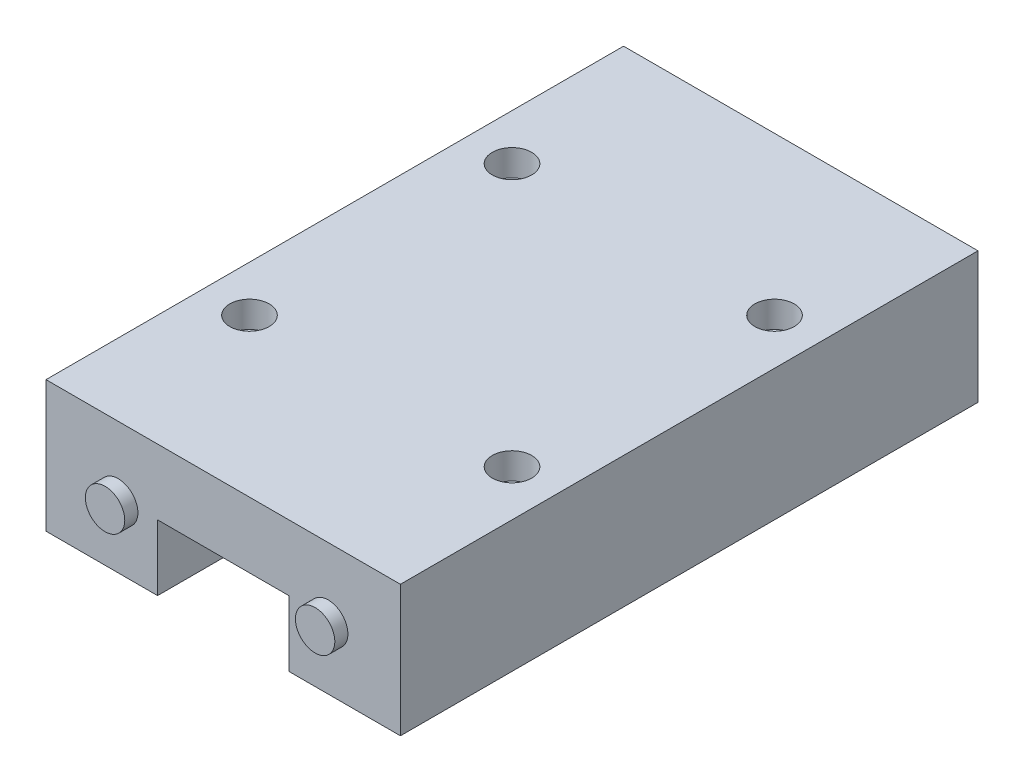
SolidWorks part; units mm, degrees
ref_plane "前基準面" through (0, 0, 0) normal (0, 0, 1) x (1, 0, 0)
ref_plane "上基準面" through (0, 0, 0) normal (0, 1, 0) x (1, 0, 0)
ref_plane "右基準面" through (0, 0, 0) normal (1, 0, 0) x (0, 0, -1)
sketch "草圖1" plane through (0, 0, 0) normal (0, 0, 1) x (1, 0, 0)
  line L0 (5, -5) -> (13.5, -5)
  line L1 (-13.5, 5) -> (13.5, 5)
  line L2 (-13.5, 5) -> (-13.5, -5)
  line L3 (-13.5, -5) -> (-5, -5)
  line L4 (13.5, 5) -> (13.5, -5)
  line L6 (-5, -5) -> (-5, 0)
  line L7 (-5, 0) -> (5, 0)
  line L8 (5, -5) -> (5, 0)
  point P4 (0, 5)
  point P6 (-13.5, 0)
  point P11 (0, 0)
  dimension "D1" = 27
  dimension "D2" = 10
  dimension "D3" = 10
  dimension "D4" = 5
extrude "填料-伸長1" add sketch "草圖1" along normal blind 44
sketch "草圖2" plane through (0, 5, 0) normal (0, 1, 0) x (1, 0, 0)
  line L0 (-13.5, -22) -> (13.5, -22) construction
  line L1 (-13.5, -44) -> (-13.5, 0) construction
  line L2 (13.5, -44) -> (13.5, 0) construction
  line L3 (0, -44) -> (0, 0) construction
  line L4 (13.5, -44) -> (-13.5, -44) construction
  circle A0 centre (-10, -32) radius 1.5
  circle A1 centre (10, -32) radius 1.5
  circle A2 centre (10, -12) radius 1.5
  circle A3 centre (-10, -12) radius 1.5
  dimension "D1" = 10
  dimension "D2" = 3
  dimension "D3" = 10
extrude "除料-伸長1" cut sketch "草圖2" against normal blind 2
sketch "草圖3" plane through (0, 0, 44) normal (0, 0, 1) x (1, 0, 0)
  line L0 (0, 5) -> (0, 0) construction
  line L1 (13.5, 5) -> (-13.5, 5) construction
  circle A0 centre (-8, -0.2841) radius 1.5
  circle A1 centre (8, -0.2841) radius 1.5
  dimension "D2" = 3
  dimension "D1" = 8
extrude "填料-伸長2" add sketch "草圖3" along normal blind 1
sketch "草圖4" plane through (0, 0, 0) normal (0, 0, -1) x (-1, 0, 0)
  line L0 (0, 0) -> (0, 5) construction
  line L1 (-13.5, 5) -> (13.5, 5) construction
  circle A0 centre (-8, 0) radius 1.5
  circle A1 centre (8, 0) radius 1.5
  dimension "D2" = 3
  dimension "D1" = 8
extrude "填料-伸長3" add sketch "草圖4" along normal blind 1
